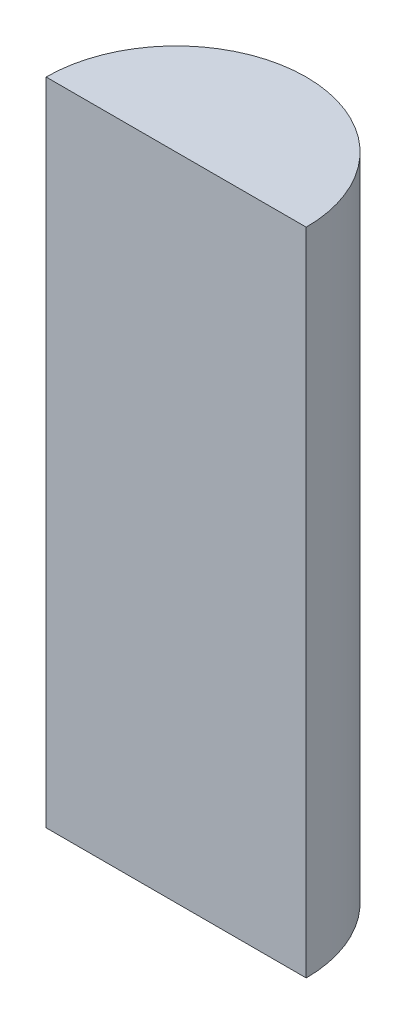
SolidWorks part; units mm, degrees
ref_plane "정면" through (0, 0, 0) normal (0, 0, 1) x (1, 0, 0)
ref_plane "윗면" through (0, 0, 0) normal (0, 1, 0) x (1, 0, 0)
ref_plane "우측면" through (0, 0, 0) normal (1, 0, 0) x (0, 0, -1)
sketch "스케치1" plane through (0, 0, 0) normal (0, 0, 1) x (1, 0, 0)
  line L0 (0, 25) -> (0, -25)
  circle A0 centre (0, 0) radius 25 construction
  circle A1 centre (0, 0) radius 25
revolve "회전-얇게4" add sketch "스케치1" angle 180 about L0
